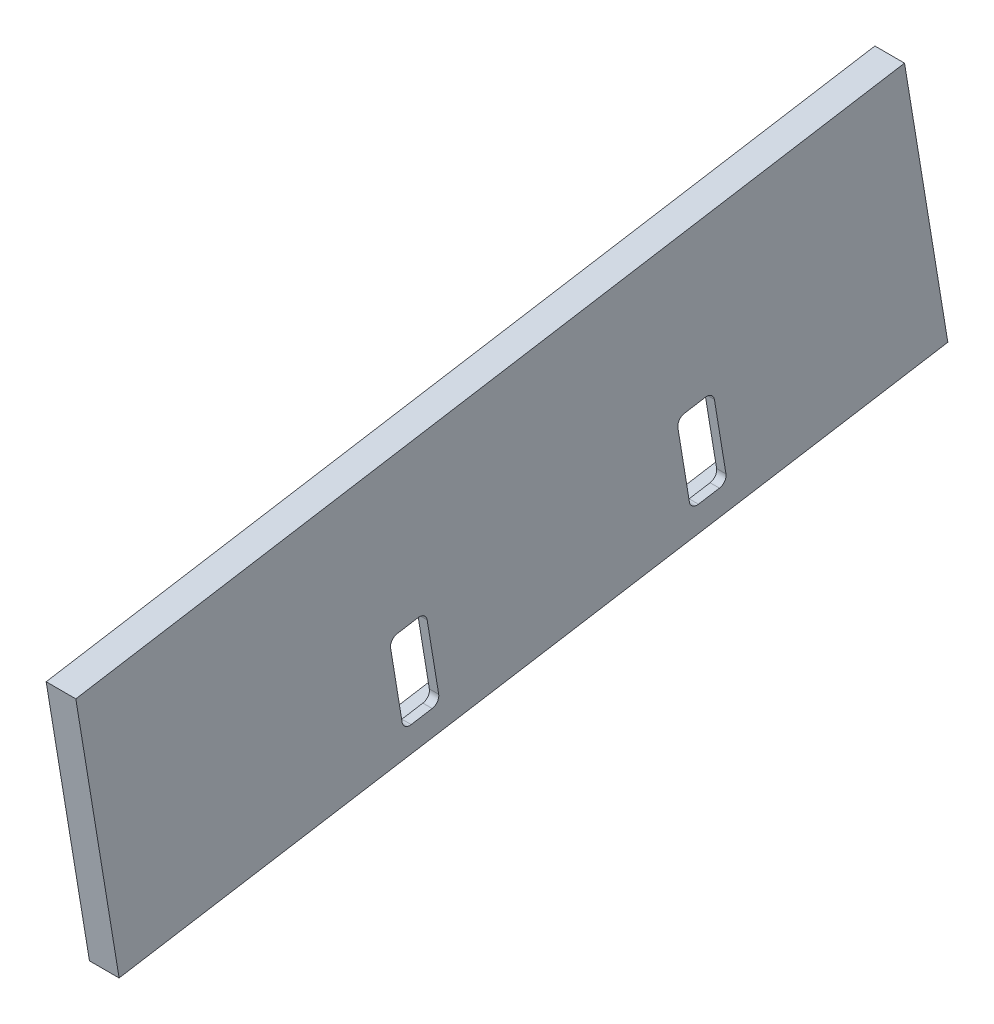
SolidWorks part; units mm, degrees
ref_plane "Front Plane" through (0, 0, 0) normal (0, 0, 1) x (1, 0, 0)
ref_plane "Top Plane" through (0, 0, 0) normal (0, 1, 0) x (1, 0, 0)
ref_plane "Right Plane" through (0, 0, 0) normal (1, 0, 0) x (0, 0, -1)
sketch "Sketch1" plane through (0, 0, 0) normal (1, 0, 0) x (0, 0, -1)
  line L0 (-1044.9231, 473.8725) -> (-1311.1763, 430.1144) construction
  line L1 (-1044.9231, 473.8725) -> (-1031.0157, 389.2502) construction
  line L2 (-1031.0157, 389.2502) -> (-1297.2689, 345.4922) construction
  line L3 (-1311.1763, 430.1144) -> (-1297.2689, 345.4922) construction
  line L4 (-1044.9231, 473.8725) -> (-1311.1763, 430.1144)
  line L5 (-1044.9231, 473.8725) -> (-1031.0157, 389.2502)
  line L6 (-1031.0157, 389.2502) -> (-1297.2689, 345.4922)
  line L7 (-1311.1763, 430.1144) -> (-1297.2689, 345.4922)
extrude "Boss-Extrude1" add sketch "Sketch1" along normal up to vertex from vertex
sketch "Sketch2" plane through (0, 0, 0) normal (1, 0, 0) x (0, 0, -1)
  line L6 (-1106.4175, 413.3061) -> (-1118.16, 411.3762) construction
  line L7 (-1101.8913, 385.7655) -> (-1106.4175, 413.3061) construction
  line L8 (-1113.6338, 383.8357) -> (-1118.16, 411.3762) construction
  line L9 (-1101.8913, 385.7655) -> (-1113.6338, 383.8357) construction
  line L10 (-1108.9239, 412.8942) -> (-1115.6536, 411.7882)
  line L11 (-1102.3032, 388.2719) -> (-1106.0056, 410.7997)
  line L12 (-1114.0457, 386.3421) -> (-1117.7481, 408.8699)
  line L13 (-1104.3977, 385.3536) -> (-1111.1274, 384.2476)
  line L16 (-1110.0256, 398.5709) -> (-1202.3175, 383.403) construction
  line L17 (-1110.0256, 398.5709) -> (-1202.3175, 383.403) construction
  line L18 (-1206.3376, 371.1741) -> (-1210.04, 393.7019)
  line L19 (-1201.2158, 397.7262) -> (-1207.9455, 396.6202)
  line L20 (-1194.5951, 373.104) -> (-1198.2975, 395.6318)
  line L21 (-1196.6896, 370.1857) -> (-1203.4193, 369.0797)
  arc A0 (-1102.3032, 388.2719) -> (-1104.3977, 385.3536) centre (-1104.8096, 387.86) cw
  arc A1 (-1114.0457, 386.3421) -> (-1111.1274, 384.2476) centre (-1111.5393, 386.754) ccw
  arc A2 (-1115.6536, 411.7882) -> (-1117.7481, 408.8699) centre (-1115.2417, 409.2818) ccw
  arc A3 (-1108.9239, 412.8942) -> (-1106.0056, 410.7997) centre (-1108.512, 410.3878) cw
  arc A4 (-1207.9455, 396.6202) -> (-1210.04, 393.7019) centre (-1207.5336, 394.1138) ccw
  arc A5 (-1201.2158, 397.7262) -> (-1198.2975, 395.6318) centre (-1200.8039, 395.2199) cw
  arc A6 (-1194.5951, 373.104) -> (-1196.6896, 370.1857) centre (-1197.1015, 372.6921) cw
  arc A7 (-1206.3376, 371.1741) -> (-1203.4193, 369.0797) centre (-1203.8312, 371.5861) ccw
  dimension "D1" = 2.54
  dimension "D3" = 93.53
  dimension "D4" = 93.53
  dimension "D2" = 2
extrude "Cut-Extrude1" cut sketch "Sketch2" against normal through all both and the other way through all
sketch "Sketch3" plane through (0, 0, 0) normal (1, 0, 0) x (0, 0, -1)
  line L0 (-1093.5296, 384.0945) -> (-1116.1067, 380.384) construction
  line L1 (-1116.1067, 380.384) -> (-1122.7412, 420.7524) construction
  line L2 (-1100.164, 424.4629) -> (-1122.7412, 420.7524) construction
  line L3 (-1093.5296, 384.0945) -> (-1100.164, 424.4629) construction
  line L4 (-1095.5031, 383.7701) -> (-1114.1332, 380.7083)
  line L5 (-1116.4311, 382.3575) -> (-1122.4168, 418.7789)
  line L6 (-1102.1376, 424.1386) -> (-1120.7676, 421.0768)
  line L7 (-1093.8539, 386.068) -> (-1099.8397, 422.4894)
  line L8 (-1110.0256, 398.5709) -> (-1202.3175, 383.403) construction
  line L9 (-1110.0256, 398.5709) -> (-1202.3175, 383.403) construction
  line L10 (-1194.4295, 408.9706) -> (-1213.0595, 405.9088)
  line L11 (-1208.723, 367.1895) -> (-1214.7087, 403.6109)
  line L12 (-1187.795, 368.6022) -> (-1206.4251, 365.5404)
  line L13 (-1186.1458, 370.9) -> (-1192.1316, 407.3214)
  arc A0 (-1102.1376, 424.1386) -> (-1099.8397, 422.4894) centre (-1101.8132, 422.165) cw
  arc A1 (-1122.4168, 418.7789) -> (-1120.7676, 421.0768) centre (-1120.4433, 419.1032) cw
  arc A2 (-1114.1332, 380.7083) -> (-1116.4311, 382.3575) centre (-1114.4575, 382.6818) cw
  arc A3 (-1095.5031, 383.7701) -> (-1093.8539, 386.068) centre (-1095.8275, 385.7436) ccw
  circle A4 centre (-1101.8132, 422.165) radius 2 construction
  arc A5 (-1214.7087, 403.6109) -> (-1213.0595, 405.9088) centre (-1212.7352, 403.9353) cw
  arc A6 (-1206.4251, 365.5404) -> (-1208.723, 367.1895) centre (-1206.7494, 367.5139) cw
  arc A7 (-1187.795, 368.6022) -> (-1186.1458, 370.9) centre (-1188.1194, 370.5757) ccw
  arc A8 (-1194.4295, 408.9706) -> (-1192.1316, 407.3214) centre (-1194.1051, 406.9971) cw
  dimension "D3" = 93.53
  dimension "D2" = 93.53
  dimension "D1" = 2
extrude "Cut-Extrude2" cut sketch "Sketch3" against normal through all from vertex at -103.127
equation "\"D4@Sketch2\"=\"D3@Sketch2\""
equation "\"D3@Sketch3\"=\"D2@Sketch3\""
